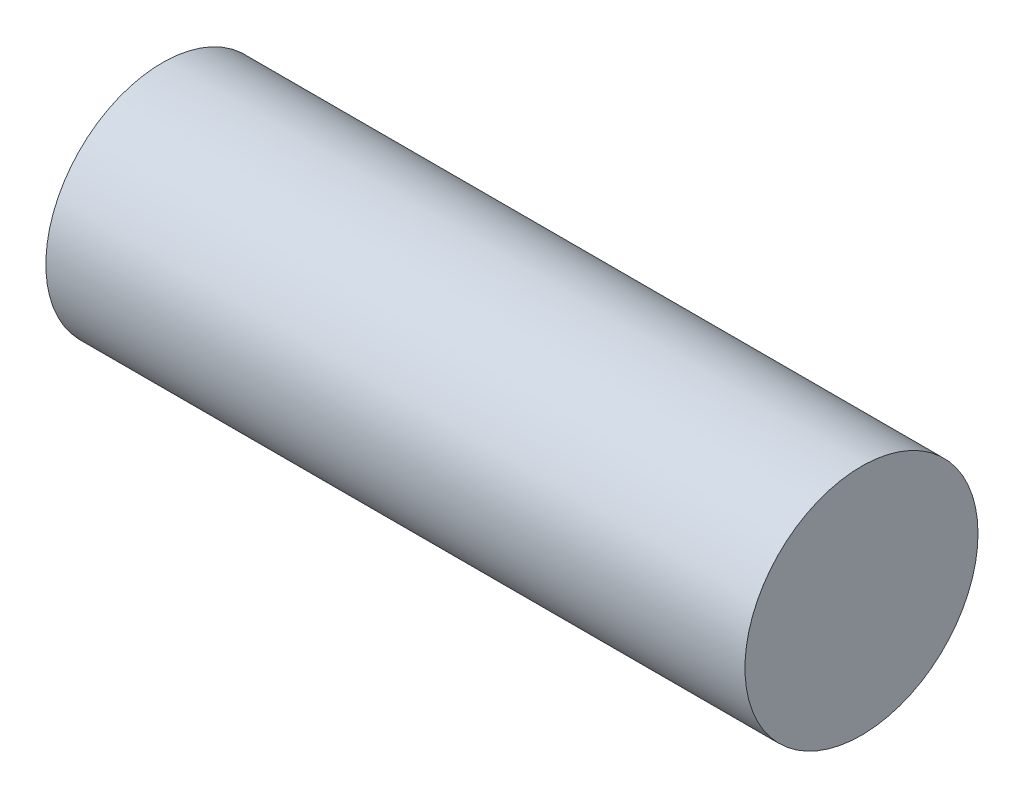
SolidWorks part; units mm, degrees
ref_plane "Front Plane" through (0, 0, 0) normal (0, 0, 1) x (1, 0, 0)
ref_plane "Top Plane" through (0, 0, 0) normal (0, 1, 0) x (1, 0, 0)
ref_plane "Right Plane" through (0, 0, 0) normal (1, 0, 0) x (0, 0, -1)
sketch "Sketch1" plane through (0, 0, 0) normal (1, 0, 0) x (0, 0, -1)
  circle A0 centre (0, 0) radius 76.2
  dimension "D1" = 152.4
extrude "Boss-Extrude1" add sketch "Sketch1" along normal blind 457.2
